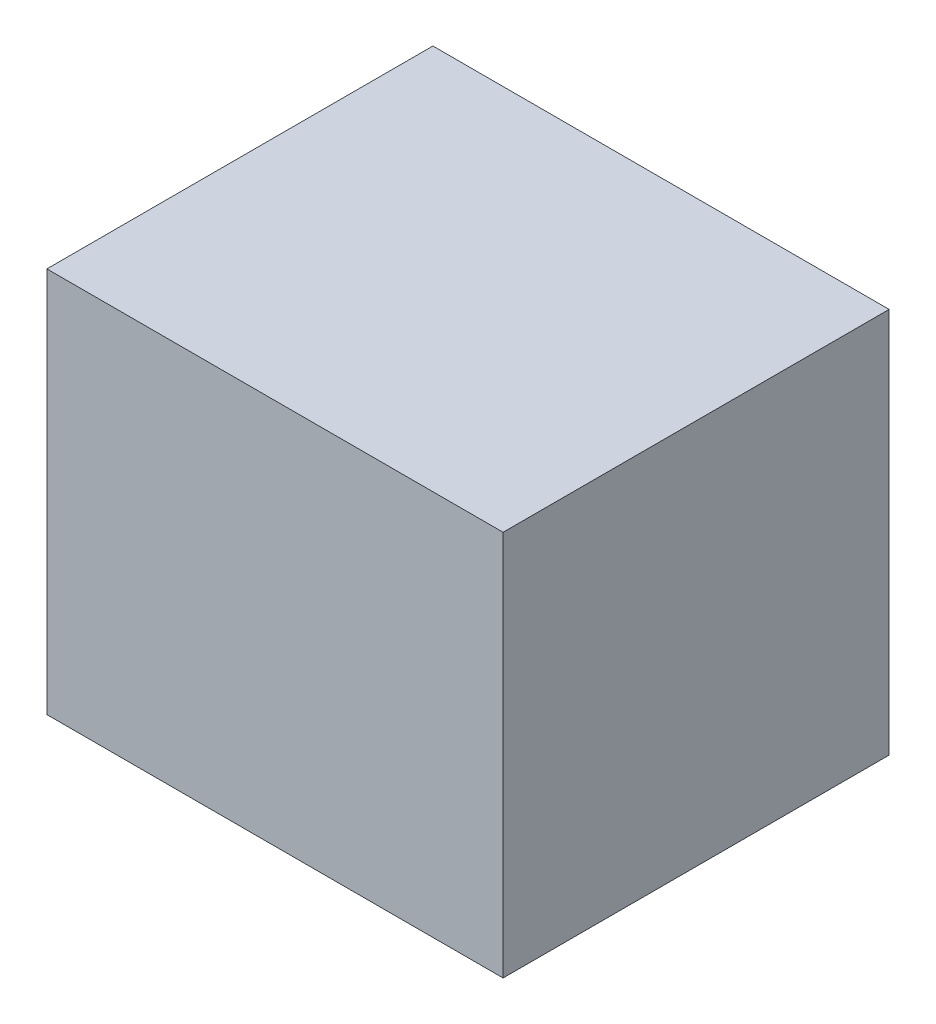
SolidWorks part; units mm, degrees
ref_plane "Front Plane" through (0, 0, 0) normal (0, 0, 1) x (1, 0, 0)
ref_plane "Top Plane" through (0, 0, 0) normal (0, 1, 0) x (1, 0, 0)
ref_plane "Right Plane" through (0, 0, 0) normal (1, 0, 0) x (0, 0, -1)
sketch "Sketch2" plane through (0, 0, 0) normal (0, 0, 1) x (1, 0, 0)
  line L1 (-325, 275) -> (325, 275)
  line L2 (-325, 275) -> (-325, -275)
  line L3 (-325, -275) -> (325, -275)
  line L4 (325, 275) -> (325, -275)
  line L5 (-325, 275) -> (325, -275) construction
  line L6 (-325, -275) -> (325, 275) construction
  point P0 (0, 0)
  dimension "D1" = 650
  dimension "D2" = 550
extrude "Boss-Extrude1" add sketch "Sketch2" along normal blind 550 and the other way blind 30 draft 45
